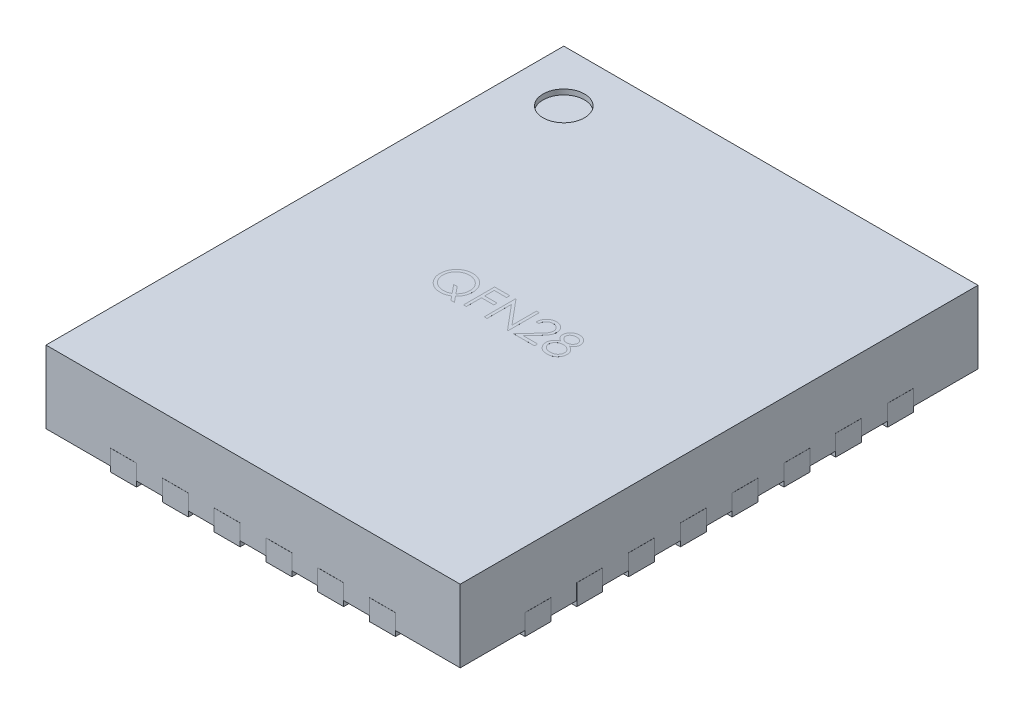
SolidWorks part; units mm, degrees
ref_plane "Front Plane" through (0, 0, 0) normal (0, 0, 1) x (1, 0, 0)
ref_plane "Top Plane" through (0, 0, 0) normal (0, 1, 0) x (1, 0, 0)
ref_plane "Right Plane" through (0, 0, 0) normal (1, 0, 0) x (0, 0, -1)
sketch "Sketch1" plane through (0, 0, 0) normal (0, 1, 0) x (1, 0, 0)
  line L1 (-2, -2.5) -> (2, -2.5)
  line L2 (-2, -2.5) -> (-2, 2.5)
  line L3 (-2, 2.5) -> (2, 2.5)
  line L4 (2, -2.5) -> (2, 2.5)
  line L5 (0, 2.5) -> (0, -2.5) construction
  line L6 (-2, 0) -> (2, 0) construction
  point P0 (0, 0)
  dimension "D1" = 5
  dimension "D2" = 4
extrude "Boss-Extrude1" add sketch "Sketch1" along normal blind 0.7
sketch "Sketch2" plane through (0, 0.7, 0) normal (0, 1, 0) x (1, 0, 0)
  line L0 (2, 2.5) -> (-2, 2.5) construction
  line L1 (-2, 2.5) -> (-2, -2.5) construction
  circle A0 centre (-1.5, 2) radius 0.2
  dimension "D1" = 0.5
  dimension "D2" = 0.5
extrude "Cut-Extrude1" cut sketch "Sketch2" against normal blind 0.05
sketch "Sketch3" plane through (0, 0, 0) normal (0, -1, 0) x (1, 0, 0)
  line L0 (-1.325, -1.475) -> (-0.975, -1.825)
  line L1 (-0.975, -1.825) -> (1.325, -1.825)
  line L2 (-1.325, -1.475) -> (-1.325, 1.825)
  line L3 (-1.325, 1.825) -> (1.325, 1.825)
  line L4 (1.325, -1.825) -> (1.325, 1.825)
  line L5 (0, 1.825) -> (0, -1.825) construction
  line L6 (-1.325, 0) -> (1.325, 0) construction
  line L7 (-1.25, 2.501) -> (-1.25, 2.101) construction
  line L8 (-2, 2.5) -> (2, 2.5) construction
  line L9 (-1.375, 2.501) -> (-1.375, 2.225)
  line L10 (-1.125, 2.501) -> (-1.125, 2.225)
  line L11 (-1.375, 2.501) -> (-1.125, 2.501)
  line L12 (-1.251, 2.101) -> (-1.249, 2.101)
  line L13 (-1.125, 2.501) -> (-1.125, 2.101) construction
  line L14 (-1.375, 2.501) -> (-1.375, 2.101) construction
  line L15 (-0.875, 2.501) -> (-0.875, 2.225)
  line L16 (-0.625, 2.501) -> (-0.625, 2.225)
  line L17 (-0.875, 2.501) -> (-0.625, 2.501)
  line L18 (-0.751, 2.101) -> (-0.749, 2.101)
  line L19 (-0.75, 2.501) -> (-0.75, 2.101) construction
  line L20 (-0.375, 2.501) -> (-0.375, 2.225)
  line L21 (-0.125, 2.501) -> (-0.125, 2.225)
  line L22 (-0.375, 2.501) -> (-0.125, 2.501)
  line L23 (-0.251, 2.101) -> (-0.249, 2.101)
  line L24 (-0.25, 2.501) -> (-0.25, 2.101) construction
  line L25 (0.125, 2.501) -> (0.125, 2.225)
  line L26 (0.375, 2.501) -> (0.375, 2.225)
  line L27 (0.125, 2.501) -> (0.375, 2.501)
  line L28 (0.249, 2.101) -> (0.251, 2.101)
  line L29 (0.25, 2.501) -> (0.25, 2.101) construction
  line L30 (0.625, 2.501) -> (0.625, 2.225)
  line L31 (0.875, 2.501) -> (0.875, 2.225)
  line L32 (0.625, 2.501) -> (0.875, 2.501)
  line L33 (0.749, 2.101) -> (0.751, 2.101)
  line L34 (0.75, 2.501) -> (0.75, 2.101) construction
  line L35 (1.125, 2.501) -> (1.125, 2.225)
  line L36 (1.375, 2.501) -> (1.375, 2.225)
  line L37 (1.125, 2.501) -> (1.375, 2.501)
  line L38 (1.249, 2.101) -> (1.251, 2.101)
  line L39 (1.25, 2.501) -> (1.25, 2.101) construction
  line L40 (1.25, -2.501) -> (1.25, -2.101) construction
  line L41 (0.75, -2.501) -> (0.75, -2.101) construction
  line L42 (0.25, -2.501) -> (0.25, -2.101) construction
  line L43 (-0.25, -2.501) -> (-0.25, -2.101) construction
  line L44 (-0.75, -2.501) -> (-0.75, -2.101) construction
  line L45 (-1.25, -2.501) -> (-1.25, -2.101) construction
  line L46 (1.249, -2.101) -> (1.251, -2.101)
  line L47 (1.125, -2.501) -> (1.375, -2.501)
  line L48 (1.375, -2.501) -> (1.375, -2.225)
  line L49 (1.125, -2.501) -> (1.125, -2.225)
  line L50 (0.749, -2.101) -> (0.751, -2.101)
  line L51 (0.625, -2.501) -> (0.875, -2.501)
  line L52 (0.875, -2.501) -> (0.875, -2.225)
  line L53 (0.625, -2.501) -> (0.625, -2.225)
  line L54 (0.249, -2.101) -> (0.251, -2.101)
  line L55 (0.125, -2.501) -> (0.375, -2.501)
  line L56 (0.375, -2.501) -> (0.375, -2.225)
  line L57 (0.125, -2.501) -> (0.125, -2.225)
  line L58 (-0.251, -2.101) -> (-0.249, -2.101)
  line L59 (-0.375, -2.501) -> (-0.125, -2.501)
  line L60 (-0.125, -2.501) -> (-0.125, -2.225)
  line L61 (-0.375, -2.501) -> (-0.375, -2.225)
  line L62 (-0.751, -2.101) -> (-0.749, -2.101)
  line L63 (-0.875, -2.501) -> (-0.625, -2.501)
  line L64 (-0.625, -2.501) -> (-0.625, -2.225)
  line L65 (-0.875, -2.501) -> (-0.875, -2.225)
  line L66 (-1.251, -2.101) -> (-1.249, -2.101)
  line L67 (-1.375, -2.501) -> (-1.125, -2.501)
  line L68 (-1.125, -2.501) -> (-1.125, -2.225)
  line L69 (-1.375, -2.501) -> (-1.375, -2.225)
  line L70 (-2.001, -1.625) -> (-1.7229, -1.625)
  line L71 (-2.001, -1.75) -> (-1.601, -1.75) construction
  line L72 (-2.001, -1.875) -> (-1.725, -1.875)
  line L73 (-1.601, -1.751) -> (-1.601, -1.749)
  line L74 (-2.001, -1.875) -> (-2.001, -1.625)
  line L75 (-2, -2.5) -> (-2, 2.5) construction
  line L76 (-2.001, -1.125) -> (-1.7229, -1.125)
  line L77 (-2.001, -1.375) -> (-1.725, -1.375)
  line L78 (-1.601, -1.251) -> (-1.601, -1.249)
  line L79 (-2.001, -1.375) -> (-2.001, -1.125)
  line L80 (-2.001, -1.25) -> (-1.601, -1.25) construction
  line L81 (-2.001, -0.625) -> (-1.7229, -0.625)
  line L82 (-2.001, -0.875) -> (-1.725, -0.875)
  line L83 (-1.601, -0.751) -> (-1.601, -0.749)
  line L84 (-2.001, -0.875) -> (-2.001, -0.625)
  line L85 (-2.001, -0.75) -> (-1.601, -0.75) construction
  line L86 (-2.001, -0.125) -> (-1.7229, -0.125)
  line L87 (-2.001, -0.375) -> (-1.725, -0.375)
  line L88 (-1.601, -0.251) -> (-1.601, -0.249)
  line L89 (-2.001, -0.375) -> (-2.001, -0.125)
  line L90 (-2.001, -0.25) -> (-1.601, -0.25) construction
  line L91 (-2.001, 0.375) -> (-1.7229, 0.375)
  line L92 (-2.001, 0.125) -> (-1.725, 0.125)
  line L93 (-1.601, 0.249) -> (-1.601, 0.251)
  line L94 (-2.001, 0.125) -> (-2.001, 0.375)
  line L95 (-2.001, 0.25) -> (-1.601, 0.25) construction
  line L96 (-2.001, 0.875) -> (-1.7229, 0.875)
  line L97 (-2.001, 0.625) -> (-1.725, 0.625)
  line L98 (-1.601, 0.749) -> (-1.601, 0.751)
  line L99 (-2.001, 0.625) -> (-2.001, 0.875)
  line L100 (-2.001, 0.75) -> (-1.601, 0.75) construction
  line L101 (-2.001, 1.375) -> (-1.7229, 1.375)
  line L102 (-2.001, 1.125) -> (-1.725, 1.125)
  line L103 (-1.601, 1.249) -> (-1.601, 1.251)
  line L104 (-2.001, 1.125) -> (-2.001, 1.375)
  line L105 (-2.001, 1.25) -> (-1.601, 1.25) construction
  line L106 (-2.001, 1.875) -> (-1.7229, 1.875)
  line L107 (-2.001, 1.625) -> (-1.725, 1.625)
  line L108 (-1.601, 1.749) -> (-1.601, 1.751)
  line L109 (-2.001, 1.625) -> (-2.001, 1.875)
  line L110 (-2.001, 1.75) -> (-1.601, 1.75) construction
  line L111 (2.001, 1.75) -> (1.601, 1.75) construction
  line L112 (2.001, 1.25) -> (1.601, 1.25) construction
  line L113 (2.001, 0.75) -> (1.601, 0.75) construction
  line L114 (2.001, 0.25) -> (1.601, 0.25) construction
  line L115 (2.001, -0.25) -> (1.601, -0.25) construction
  line L116 (2.001, -0.75) -> (1.601, -0.75) construction
  line L117 (2.001, -1.25) -> (1.601, -1.25) construction
  line L118 (2.001, -1.75) -> (1.601, -1.75) construction
  line L119 (2.001, 1.625) -> (2.001, 1.875)
  line L120 (1.601, 1.749) -> (1.601, 1.751)
  line L121 (2.001, 1.625) -> (1.725, 1.625)
  line L122 (2.001, 1.875) -> (1.7229, 1.875)
  line L123 (2.001, 1.125) -> (2.001, 1.375)
  line L124 (1.601, 1.249) -> (1.601, 1.251)
  line L125 (2.001, 1.125) -> (1.725, 1.125)
  line L126 (2.001, 1.375) -> (1.7229, 1.375)
  line L127 (2.001, 0.625) -> (2.001, 0.875)
  line L128 (1.601, 0.749) -> (1.601, 0.751)
  line L129 (2.001, 0.625) -> (1.725, 0.625)
  line L130 (2.001, 0.875) -> (1.7229, 0.875)
  line L131 (2.001, 0.125) -> (2.001, 0.375)
  line L132 (1.601, 0.249) -> (1.601, 0.251)
  line L133 (2.001, 0.125) -> (1.725, 0.125)
  line L134 (2.001, 0.375) -> (1.7229, 0.375)
  line L135 (2.001, -0.375) -> (2.001, -0.125)
  line L136 (1.601, -0.251) -> (1.601, -0.249)
  line L137 (2.001, -0.375) -> (1.725, -0.375)
  line L138 (2.001, -0.125) -> (1.7229, -0.125)
  line L139 (2.001, -0.875) -> (2.001, -0.625)
  line L140 (1.601, -0.751) -> (1.601, -0.749)
  line L141 (2.001, -0.875) -> (1.725, -0.875)
  line L142 (2.001, -0.625) -> (1.7229, -0.625)
  line L143 (2.001, -1.375) -> (2.001, -1.125)
  line L144 (1.601, -1.251) -> (1.601, -1.249)
  line L145 (2.001, -1.375) -> (1.725, -1.375)
  line L146 (2.001, -1.125) -> (1.7229, -1.125)
  line L147 (2.001, -1.875) -> (2.001, -1.625)
  line L148 (1.601, -1.751) -> (1.601, -1.749)
  line L149 (2.001, -1.875) -> (1.725, -1.875)
  line L150 (2.001, -1.625) -> (1.7229, -1.625)
  arc A0 (-1.125, 2.225) -> (-1.249, 2.101) centre (-1.249, 2.225) cw
  arc A1 (-1.375, 2.225) -> (-1.251, 2.101) centre (-1.251, 2.225) ccw
  arc A2 (-0.625, 2.225) -> (-0.749, 2.101) centre (-0.749, 2.225) cw
  arc A3 (-0.875, 2.225) -> (-0.751, 2.101) centre (-0.751, 2.225) ccw
  arc A4 (-0.125, 2.225) -> (-0.249, 2.101) centre (-0.249, 2.225) cw
  arc A5 (-0.375, 2.225) -> (-0.251, 2.101) centre (-0.251, 2.225) ccw
  arc A6 (0.375, 2.225) -> (0.251, 2.101) centre (0.251, 2.225) cw
  arc A7 (0.125, 2.225) -> (0.249, 2.101) centre (0.249, 2.225) ccw
  arc A8 (0.875, 2.225) -> (0.751, 2.101) centre (0.751, 2.225) cw
  arc A9 (0.625, 2.225) -> (0.749, 2.101) centre (0.749, 2.225) ccw
  arc A10 (1.375, 2.225) -> (1.251, 2.101) centre (1.251, 2.225) cw
  arc A11 (1.125, 2.225) -> (1.249, 2.101) centre (1.249, 2.225) ccw
  arc A12 (1.125, -2.225) -> (1.249, -2.101) centre (1.249, -2.225) cw
  arc A13 (1.375, -2.225) -> (1.251, -2.101) centre (1.251, -2.225) ccw
  arc A14 (0.625, -2.225) -> (0.749, -2.101) centre (0.749, -2.225) cw
  arc A15 (0.875, -2.225) -> (0.751, -2.101) centre (0.751, -2.225) ccw
  arc A16 (0.125, -2.225) -> (0.249, -2.101) centre (0.249, -2.225) cw
  arc A17 (0.375, -2.225) -> (0.251, -2.101) centre (0.251, -2.225) ccw
  arc A18 (-0.375, -2.225) -> (-0.251, -2.101) centre (-0.251, -2.225) cw
  arc A19 (-0.125, -2.225) -> (-0.249, -2.101) centre (-0.249, -2.225) ccw
  arc A20 (-0.875, -2.225) -> (-0.751, -2.101) centre (-0.751, -2.225) cw
  arc A21 (-0.625, -2.225) -> (-0.749, -2.101) centre (-0.749, -2.225) ccw
  arc A22 (-1.375, -2.225) -> (-1.251, -2.101) centre (-1.251, -2.225) cw
  arc A23 (-1.125, -2.225) -> (-1.249, -2.101) centre (-1.249, -2.225) ccw
  arc A24 (-1.725, -1.875) -> (-1.601, -1.751) centre (-1.725, -1.751) ccw
  arc A25 (-1.7229, -1.625) -> (-1.601, -1.749) centre (-1.725, -1.749) cw
  arc A26 (-1.725, -1.375) -> (-1.601, -1.251) centre (-1.725, -1.251) ccw
  arc A27 (-1.7229, -1.125) -> (-1.601, -1.249) centre (-1.725, -1.249) cw
  arc A28 (-1.725, -0.875) -> (-1.601, -0.751) centre (-1.725, -0.751) ccw
  arc A29 (-1.7229, -0.625) -> (-1.601, -0.749) centre (-1.725, -0.749) cw
  arc A30 (-1.725, -0.375) -> (-1.601, -0.251) centre (-1.725, -0.251) ccw
  arc A31 (-1.7229, -0.125) -> (-1.601, -0.249) centre (-1.725, -0.249) cw
  arc A32 (-1.725, 0.125) -> (-1.601, 0.249) centre (-1.725, 0.249) ccw
  arc A33 (-1.7229, 0.375) -> (-1.601, 0.251) centre (-1.725, 0.251) cw
  arc A34 (-1.725, 0.625) -> (-1.601, 0.749) centre (-1.725, 0.749) ccw
  arc A35 (-1.7229, 0.875) -> (-1.601, 0.751) centre (-1.725, 0.751) cw
  arc A36 (-1.725, 1.125) -> (-1.601, 1.249) centre (-1.725, 1.249) ccw
  arc A37 (-1.7229, 1.375) -> (-1.601, 1.251) centre (-1.725, 1.251) cw
  arc A38 (-1.725, 1.625) -> (-1.601, 1.749) centre (-1.725, 1.749) ccw
  arc A39 (-1.7229, 1.875) -> (-1.601, 1.751) centre (-1.725, 1.751) cw
  arc A40 (1.7229, 1.875) -> (1.601, 1.751) centre (1.725, 1.751) ccw
  arc A41 (1.725, 1.625) -> (1.601, 1.749) centre (1.725, 1.749) cw
  arc A42 (1.7229, 1.375) -> (1.601, 1.251) centre (1.725, 1.251) ccw
  arc A43 (1.725, 1.125) -> (1.601, 1.249) centre (1.725, 1.249) cw
  arc A44 (1.7229, 0.875) -> (1.601, 0.751) centre (1.725, 0.751) ccw
  arc A45 (1.725, 0.625) -> (1.601, 0.749) centre (1.725, 0.749) cw
  arc A46 (1.7229, 0.375) -> (1.601, 0.251) centre (1.725, 0.251) ccw
  arc A47 (1.725, 0.125) -> (1.601, 0.249) centre (1.725, 0.249) cw
  arc A48 (1.7229, -0.125) -> (1.601, -0.249) centre (1.725, -0.249) ccw
  arc A49 (1.725, -0.375) -> (1.601, -0.251) centre (1.725, -0.251) cw
  arc A50 (1.7229, -0.625) -> (1.601, -0.749) centre (1.725, -0.749) ccw
  arc A51 (1.725, -0.875) -> (1.601, -0.751) centre (1.725, -0.751) cw
  arc A52 (1.7229, -1.125) -> (1.601, -1.249) centre (1.725, -1.249) ccw
  arc A53 (1.725, -1.375) -> (1.601, -1.251) centre (1.725, -1.251) cw
  arc A54 (1.7229, -1.625) -> (1.601, -1.749) centre (1.725, -1.749) ccw
  arc A55 (1.725, -1.875) -> (1.601, -1.751) centre (1.725, -1.751) cw
  point P0 (0, 0)
  point P2 (-1.325, -1.825)
  point P147 (-1.601, -1.75)
  dimension "D9" = 0.124
  dimension "D1" = 3.65
  dimension "D2" = 2.65
  dimension "D3" = 0.001
  dimension "D4" = 0.4
  dimension "D6" = 1.25
  dimension "D11" = 0.4
  dimension "D12" = 0.001
  dimension "D13" = 1.75
  dimension "D7" = 0.125
  dimension "D8" = 0.125
  dimension "D10" = 6
  dimension "D14" = 8
extrude "Boss-Extrude2" add sketch "Sketch3" along normal blind 0.05 and the other way blind 0.15
sketch "Sketch4" plane through (0, 0.7, 0) normal (0, 1, 0) x (1, 0, 0)
  text T0 "QFN28" font "Century Gothic" height 0.3
extrude "Boss-Extrude3" add sketch "Sketch4" along normal blind 0.0001
